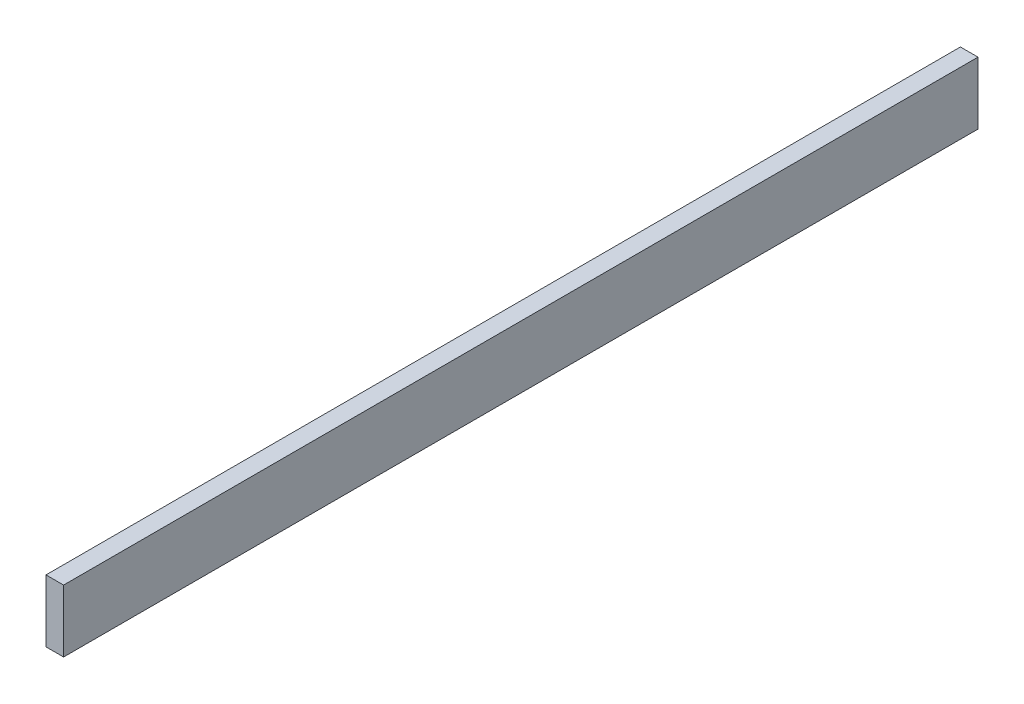
SolidWorks part; units mm, degrees
ref_plane "Front Plane" through (0, 0, 0) normal (0, 0, 1) x (1, 0, 0)
ref_plane "Top Plane" through (0, 0, 0) normal (0, 1, 0) x (1, 0, 0)
ref_plane "Right Plane" through (0, 0, 0) normal (1, 0, 0) x (0, 0, -1)
other "Configuration Table"
sketch "Sketch1" plane through (0, 0, 0) normal (0, 0, 1) x (1, 0, 0)
  line L1 (0, 14) -> (12.7, 14)
  line L2 (0, 14) -> (0, 59)
  line L3 (0, 59) -> (12.7, 59)
  line L4 (12.7, 14) -> (12.7, 59)
extrude "CEK_icecek_ray_ic_profil_sol_1" add sketch "Sketch1" against normal blind 660 separate body
